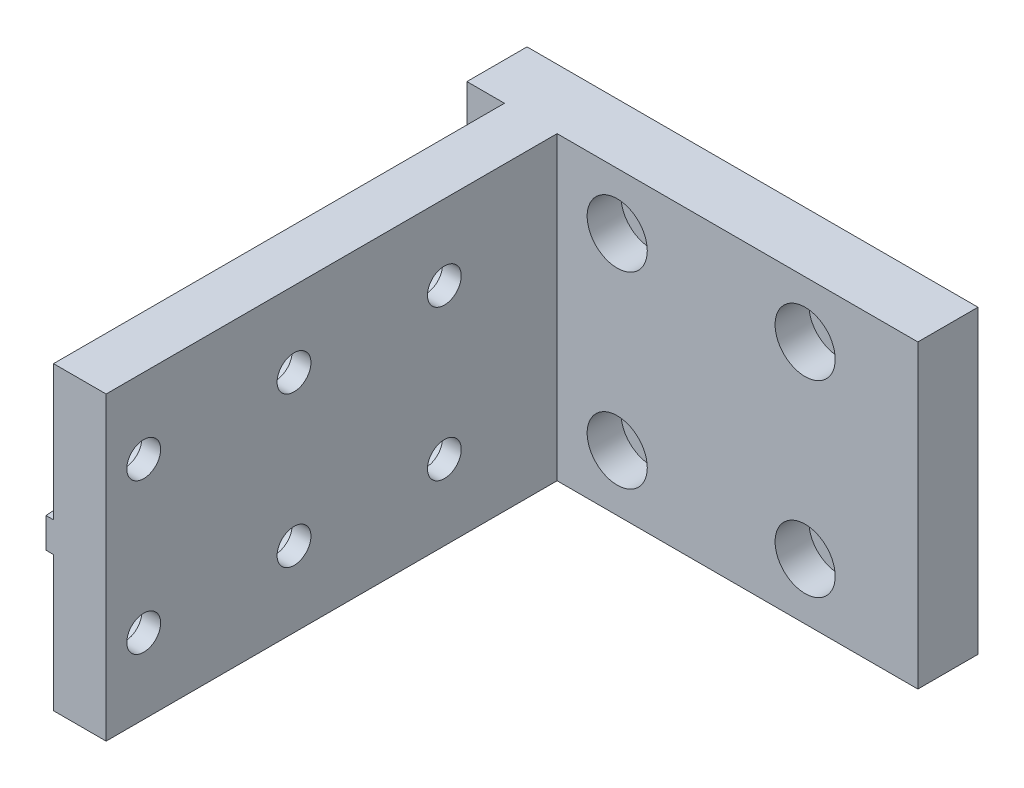
SolidWorks part; units mm, degrees
ref_plane "前视基准面" through (0, 0, 0) normal (0, 0, 1) x (1, 0, 0)
ref_plane "上视基准面" through (0, 0, 0) normal (0, 1, 0) x (1, 0, 0)
ref_plane "右视基准面" through (0, 0, 0) normal (1, 0, 0) x (0, 0, -1)
sketch "草图1" plane through (0, 0, 0) normal (0, 0, 1) x (1, 0, 0)
  line L1 (-30, 20) -> (30, 20)
  line L2 (-30, 20) -> (-30, -20)
  line L3 (-30, -20) -> (30, -20)
  line L4 (30, 20) -> (30, -20)
  line L5 (-30, 20) -> (30, -20) construction
  line L6 (-30, -20) -> (30, 20) construction
  point P0 (0, 0)
  dimension "D1" = 60
  dimension "D2" = 40
extrude "凸台-拉伸2" add sketch "草图1" along normal blind 8
sketch "草图3" plane through (0, 0, 8) normal (0, 0, 1) x (1, 0, 0)
  line L0 (30, -20) -> (30, 20) construction
  line L2 (30, 20) -> (-30, 20) construction
  line L3 (-30, -20) -> (30, -20) construction
  circle A0 centre (15, 12.5) radius 2.25
  circle A1 centre (15, -12.5) radius 2.25
  circle A2 centre (-10, 12.5) radius 2.25
  circle A3 centre (-10, -12.5) radius 2.25
  dimension "D1" = 4.5
  dimension "D2" = 4.5
  dimension "D5" = 7.5
  dimension "D7" = 4.5
  dimension "D8" = 4.5
  dimension "D9" = 7.5
  dimension "D11" = 25
  dimension "D12" = 25
  dimension "D3" = 15
  dimension "D4" = 7.5
  dimension "D6" = 15
  dimension "D10" = 7.5
extrude "切除-拉伸1" cut sketch "草图3" against normal blind 8
sketch "草图4" plane through (0, 0, 8) normal (0, 0, 1) x (1, 0, 0)
  circle A0 centre (15, 12.5) radius 4
  circle A1 centre (15, -12.5) radius 4
  circle A2 centre (-10, 12.5) radius 4
  circle A3 centre (-10, -12.5) radius 4
  dimension "D1" = 8
  dimension "D2" = 8
  dimension "D3" = 8
  dimension "D4" = 8
extrude "切除-拉伸2" cut sketch "草图4" against normal blind 4.5
sketch "草图5" plane through (0, 0, 8) normal (0, 0, 1) x (1, 0, 0)
  line L0 (-25, 20) -> (-18, 20)
  line L1 (30, 20) -> (-30, 20) construction
  line L2 (-18, 20) -> (-18, -20)
  line L3 (-30, -20) -> (30, -20) construction
  line L4 (-18, -20) -> (-25, -20)
  line L5 (-25, -20) -> (-25, 20)
  line L6 (-30, 20) -> (-30, -20) construction
  dimension "D1" = 7
  dimension "D2" = 5
extrude "凸台-拉伸3" add sketch "草图5" along normal blind 60
sketch "草图6" plane through (-25, 0, 0) normal (-1, 0, 0) x (0, 0, 1)
  line L0 (68, 20) -> (68, -20) construction
  line L1 (68, 20) -> (8, 20) construction
  line L2 (68, -20) -> (8, -20) construction
  circle A0 centre (63, 10) radius 2.25
  circle A1 centre (63, -10) radius 2.25
  dimension "D1" = 4.5
  dimension "D2" = 4.5
  dimension "D5" = 5
  dimension "D3" = 5
  dimension "D4" = 10
  dimension "D6" = 10
extrude "切除-拉伸3" cut sketch "草图6" against normal up to next
sketch "草图7" plane through (-25, 0, 0) normal (-1, 0, 0) x (0, 0, 1)
  circle A0 centre (63, 10) radius 4
  circle A1 centre (63, -10) radius 4
  dimension "D1" = 8
  dimension "D2" = 8
extrude "切除-拉伸4" cut sketch "草图7" against normal blind 4.5
pattern_linear "阵列(线性)1" count 3 spacing 20 along (0, 0, -1) of "切除-拉伸3", "切除-拉伸4"
sketch "草图8" plane through (0, 0, 8) normal (0, 0, 1) x (1, 0, 0)
  line L0 (-30, 2) -> (-30, -2)
  line L1 (-30, 20) -> (-30, -20) construction
  line L2 (-30, -2) -> (-25, -2)
  line L3 (-25, 20) -> (-25, -20) construction
  line L4 (-25, -2) -> (-25, 2)
  line L5 (-25, 2) -> (-30, 2)
  line L6 (-30, -20) -> (-25, -20) construction
  dimension "D1" = 4
  dimension "D2" = 18
sketch "草图9" plane through (0, 0, 68) normal (0, 0, 1) x (1, 0, 0)
  line L0 (-25, 2) -> (-26, 2)
  line L1 (-25, 20) -> (-25, -20) construction
  line L2 (-26, 2) -> (-26, -2)
  line L3 (-26, -2) -> (-25, -2)
  line L4 (-25, -2) -> (-25, 2)
  line L5 (-25, -20) -> (-18, -20) construction
  dimension "D1" = 1
  dimension "D2" = 4
  dimension "D3" = 18
loft "放样2" add profiles "草图8", "草图9"
